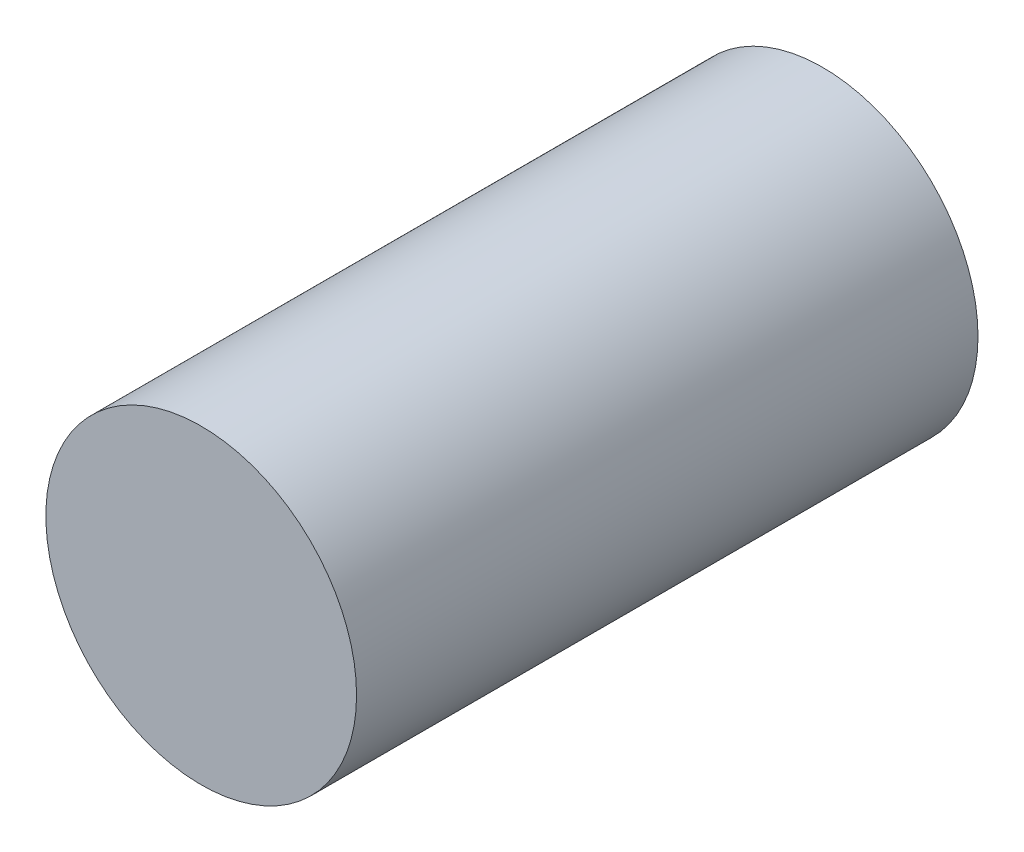
SolidWorks part; units mm, degrees
ref_plane "Front Plane" through (0, 0, 0) normal (0, 0, 1) x (1, 0, 0)
ref_plane "Top Plane" through (0, 0, 0) normal (0, 1, 0) x (1, 0, 0)
ref_plane "Right Plane" through (0, 0, 0) normal (1, 0, 0) x (0, 0, -1)
sketch "Sketch1" plane through (0, 0, 0) normal (0, 0, 1) x (1, 0, 0)
  circle A0 centre (0, 0) radius 15
  dimension "D1" = 30
extrude "Boss-Extrude1" add sketch "Sketch1" along normal blind 60
